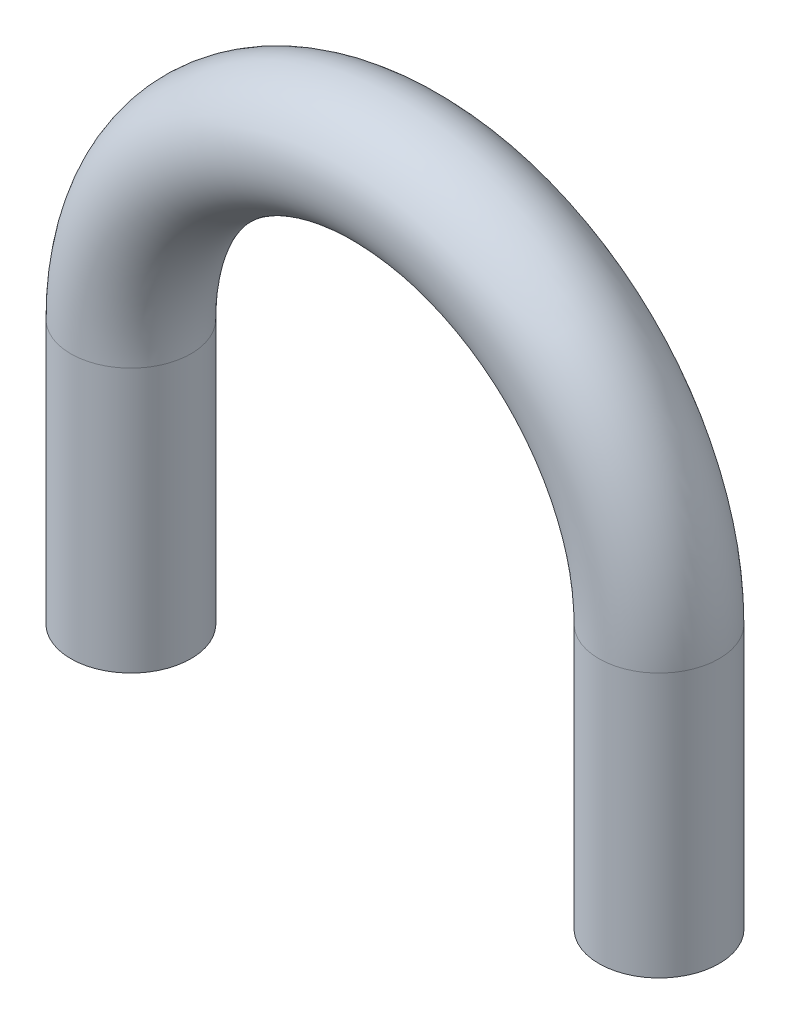
SolidWorks part; units mm, degrees
material "Cobre"
ref_plane "Alzado" through (0, 0, 0) normal (0, 0, 1) x (1, 0, 0)
ref_plane "Planta" through (0, 0, 0) normal (0, 1, 0) x (1, 0, 0)
ref_plane "Vista lateral" through (0, 0, 0) normal (1, 0, 0) x (0, 0, -1)
sketch "Croquis1" plane through (0, 0, 0) normal (0, 0, 1) x (1, 0, 0)
  line L0 (-2, 0) -> (-2, 2)
  line L1 (2, 0) -> (2, 2)
  arc A0 (-2, 2) -> (2, 2) centre (0, 2) cw
  dimension "D3" = 2
  dimension "D1" = 4
  dimension "D2" = 2
sweep "Barrer1" add path "Croquis1" circular profile diameter 0.91 parameters "D3"=0.91
